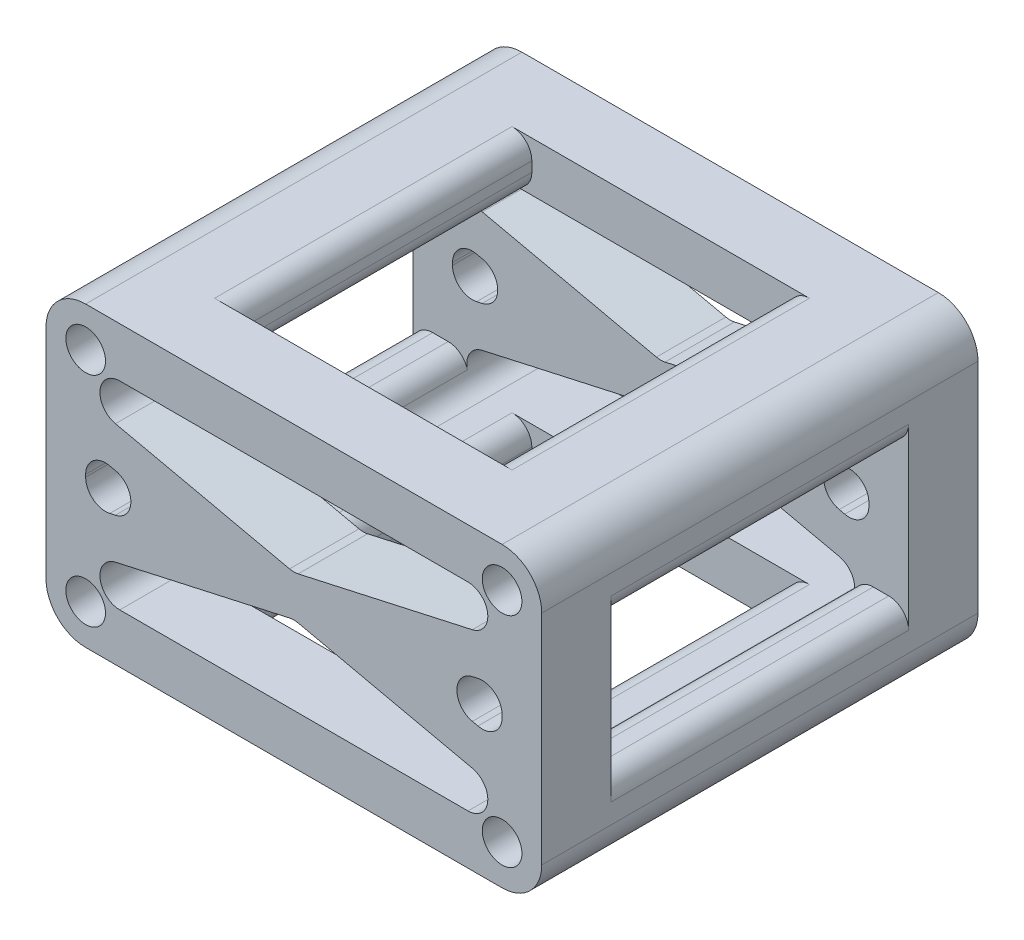
SolidWorks part; units mm, degrees
material "ABS"
ref_plane "Front" through (0, 0, 0) normal (0, 0, 1) x (1, 0, 0)
ref_plane "Top" through (0, 0, 0) normal (0, 1, 0) x (1, 0, 0)
ref_plane "Right" through (0, 0, 0) normal (1, 0, 0) x (0, 0, -1)
sketch "草图1" plane through (0, 0, 0) normal (0, 0, 1) x (1, 0, 0)
  line L1 (-12.5, -7.5) -> (12.5, -7.5)
  line L2 (-12.5, -7.5) -> (-12.5, 7.5)
  line L3 (-12.5, 7.5) -> (12.5, 7.5)
  line L4 (12.5, -7.5) -> (12.5, 7.5)
  line L5 (0, 7.5) -> (0, -7.5) construction
  line L6 (-12.5, 0) -> (12.5, 0) construction
  point P0 (0, 0)
  dimension "D1" = 15
  dimension "D2" = 25
extrude "凸台-拉伸1" add sketch "草图1" along normal blind 22
sketch "草图2" plane through (0, 0, 22) normal (0, 0, 1) x (1, 0, 0)
  line L0 (-3.0403, 0) -> (3.9486, 0) construction
  line L1 (0, 2.52) -> (0, 0) construction
  line L2 (-10.5, 0.0623) -> (-10.5, -0.0623)
  line L3 (-9.2831, -1.0385) -> (-9.0026, -0.9762)
  line L4 (-9.2831, 1.0385) -> (-9.0026, 0.9762)
  line L5 (0.2169, 1.0726) -> (8.9974, 3.0238)
  line L6 (-8.9974, 3.0238) -> (-0.2169, 1.0726)
  line L7 (9.2831, 1.0385) -> (9.0026, 0.9762)
  line L8 (9.2831, -1.0385) -> (9.0026, -0.9762)
  line L9 (8.7805, -5) -> (-8.7805, -5)
  line L10 (-8.9974, -3.0238) -> (-0.2169, -1.0726)
  line L11 (0.2169, -1.0726) -> (8.9974, -3.0238)
  line L12 (8.7805, 5) -> (-8.7805, 5)
  line L13 (10.5, 0.0623) -> (10.5, -0.0623)
  line L15 (12.5, -7.5) -> (12.5, 7.5) construction
  arc A0 (10.5, -0.0623) -> (9.2831, -1.0385) centre (9.5, -0.0623) cw
  arc A1 (10.5, 0.0623) -> (9.2831, 1.0385) centre (9.5, 0.0623) ccw
  arc A2 (-9.0026, 0.9762) -> (-9.0026, -0.9762) centre (-9.2195, 0) cw
  arc A3 (-10.5, 0.0623) -> (-9.2831, 1.0385) centre (-9.5, 0.0623) cw
  arc A4 (-10.5, -0.0623) -> (-9.2831, -1.0385) centre (-9.5, -0.0623) ccw
  arc A5 (0.2169, 1.0726) -> (-0.2169, 1.0726) centre (0, 2.0488) cw
  arc A6 (-8.9974, 3.0238) -> (-8.7805, 5) centre (-8.7805, 4) cw
  arc A7 (9.0026, 0.9762) -> (9.0026, -0.9762) centre (9.2195, 0) ccw
  arc A8 (8.7805, -5) -> (8.9974, -3.0238) centre (8.7805, -4) ccw
  arc A9 (-8.9974, -3.0238) -> (-8.7805, -5) centre (-8.7805, -4) ccw
  arc A10 (0.2169, -1.0726) -> (-0.2169, -1.0726) centre (0, -2.0488) ccw
  arc A11 (8.7805, 5) -> (8.9974, 3.0238) centre (8.7805, 4) cw
  point P6 (-10.4472, 4.1056)
  point P7 (9.5528, -5.8944)
  point P8 (-9.5528, 5.8944)
  point P9 (10.4472, -4.1056)
  point P10 (-9.5528, -5.8944)
  point P11 (10.4472, 4.1056)
  point P12 (-10.4472, -4.1056)
  point P13 (9.5528, 5.8944)
  point P14 (-10.5211, -6.8779)
  point P15 (11.4789, 5.1221)
  point P16 (-11.4789, 5.1221)
  point P17 (10.5211, -6.8779)
  point P18 (-11.4789, -5.1221)
  point P19 (10.5211, 6.8779)
  point P20 (-10.5211, 6.8779)
  point P21 (11.4789, -5.1221)
  dimension "D2" = 1
  dimension "D1" = 2
fillet "圆角4" radius 2 4 edges at (-12.5, 7.5, 11) (12.5, -7.5, 11) (12.5, 7.5, 11) (-12.5, -7.5, 11)
extrude "切除-拉伸3" cut sketch "草图2" against normal through all both and the other way through all
sketch "草图3" plane through (0, 0, 22) normal (0, 0, 1) x (1, 0, 0)
  line L0 (0, 3.0049) -> (0, -1.7372) construction
  line L1 (-3.0112, 0) -> (3.1966, 0) construction
  circle A0 centre (-10.5, 5.5) radius 1
  circle A1 centre (10.5, 5.5) radius 1
  circle A2 centre (10.5, -5.5) radius 1
  circle A3 centre (-10.5, -5.5) radius 1
  dimension "D1" = 2
extrude "切除-拉伸4" cut sketch "草图3" against normal through all both and the other way through all
sketch "草图4" plane through (0, 7.5, 0) normal (0, 1, 0) x (1, 0, 0)
  line L1 (-6.5, -18.5) -> (6.5, -18.5)
  line L2 (-6.5, -18.5) -> (-6.5, -3.5)
  line L3 (-6.5, -3.5) -> (6.5, -3.5)
  line L4 (6.5, -18.5) -> (6.5, -3.5)
  line L5 (-6.5, -18.5) -> (6.5, -3.5) construction
  line L6 (-6.5, -3.5) -> (6.5, -18.5) construction
  point P0 (0, -11)
  point P5 (0, 0)
  dimension "D1" = 13
  dimension "D2" = 15
extrude "切除-拉伸5" cut sketch "草图4" against normal through all both and the other way through all
sketch "草图5" plane through (-12.5, 0, 0) normal (-1, 0, 0) x (0, 0, 1)
  line L1 (3.5, -3.5) -> (18.5, -3.5)
  line L2 (3.5, -3.5) -> (3.5, 3.5)
  line L3 (3.5, 3.5) -> (18.5, 3.5)
  line L4 (18.5, -3.5) -> (18.5, 3.5)
  line L5 (3.5, -3.5) -> (18.5, 3.5) construction
  line L6 (3.5, 3.5) -> (18.5, -3.5) construction
  point P0 (11, 0)
  point P5 (0, 0)
  point P7 (9.9078, 0)
  point P8 (11, 0)
  point P9 (11, 0)
  point P10 (10.556, 0)
  dimension "D1" = 15
  dimension "D2" = 7
extrude "切除-拉伸6" cut sketch "草图5" against normal through all
fillet "圆角5" radius 1 16 edges at (-6.5, -7.5, 11) (6.5, -7.5, 11) (-6.5, 7.5, 11) (6.5, 7.5, 11) (-12.5, -3.5, 11) (-12.5, 3.5, 11) (12.5, 3.5, 11) (12.5, -3.5, 11) (6.5, -5, 11) (-6.5, -5, 11) (6.5, 5, 11) (-6.5, 5, 11) (-9.6465, -3.5, 11) (-9.6465, 3.5, 11) (9.6465, 3.5, 11) (9.6465, -3.5, 11)
